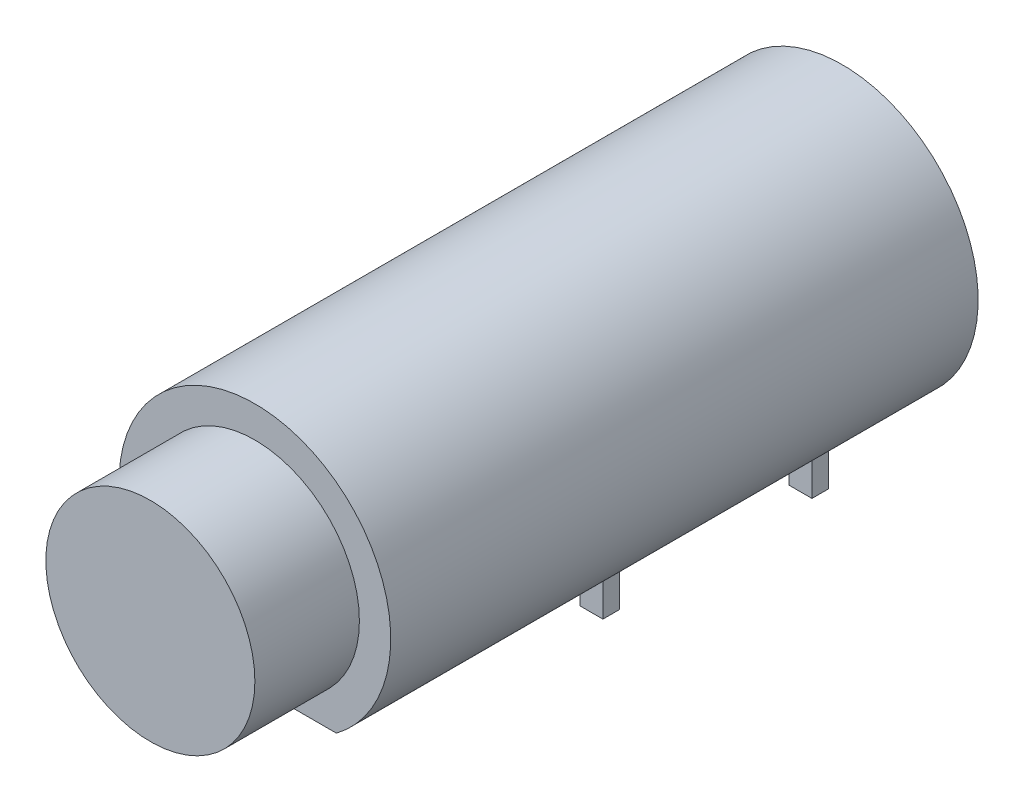
SolidWorks part; units mm, degrees
ref_plane "前视基准面" through (0, 0, 0) normal (0, 0, 1) x (1, 0, 0)
ref_plane "上视基准面" through (0, 0, 0) normal (0, 1, 0) x (1, 0, 0)
ref_plane "右视基准面" through (0, 0, 0) normal (1, 0, 0) x (0, 0, -1)
sketch "草图1" plane through (0, 0, 0) normal (0, 0, 1) x (1, 0, 0)
  line L0 (-3.9, -5.2) -> (3.9, -5.2)
  line L1 (0, -11.4382) -> (0, 5.2977) construction
  arc A0 (3.9, -5.2) -> (-3.9, -5.2) centre (0, 0) ccw
  dimension "D1" = 5.2
  dimension "D2" = 6.5
extrude "凸台-拉伸1" add sketch "草图1" along normal blind 33.1
sketch "草图2" plane through (0, 0, 33.1) normal (0, 0, 1) x (1, 0, 0)
  line L0 (-3.9, -5.2) -> (3.9, -5.2) construction
  line L1 (-3.9, -5.2) -> (3.9, -5.2)
  circle A0 centre (0, 0) radius 5
  arc A1 (3.9, -5.2) -> (-3.9, -5.2) centre (0, 0) ccw construction
  arc A2 (3.9, -5.2) -> (-3.9, -5.2) centre (0, 0) ccw
  dimension "D1" = 10
extrude "切除-拉伸1" cut sketch "草图2" against normal blind 5
sketch "草图3" plane through (0, -5.2, 0) normal (0, -1, 0) x (1, 0, 0)
  line L0 (0, -6.0259) -> (0, 38.084) construction
  line L1 (-8.6651, 11.6) -> (9.9311, 11.6) construction
  line L2 (-0.55, 12) -> (0.55, 12)
  line L3 (-0.55, 12) -> (-0.55, 11.2)
  line L4 (-0.55, 11.2) -> (0.55, 11.2)
  line L5 (0.55, 12) -> (0.55, 11.2)
  line L6 (-3.9, 28.1) -> (3.9, 28.1) construction
  line L7 (-0.55, 2) -> (0.55, 2)
  line L8 (-0.55, 2) -> (-0.55, 1.2)
  line L9 (-0.55, 1.2) -> (0.55, 1.2)
  line L10 (0.55, 2) -> (0.55, 1.2)
  line L11 (-8.6651, 1.6) -> (9.9311, 1.6) construction
  dimension "D1" = 16.5
  dimension "D2" = 0.8
  dimension "D3" = 1.1
  dimension "D4" = 2
extrude "凸台-拉伸2" add sketch "草图3" along normal blind 5
